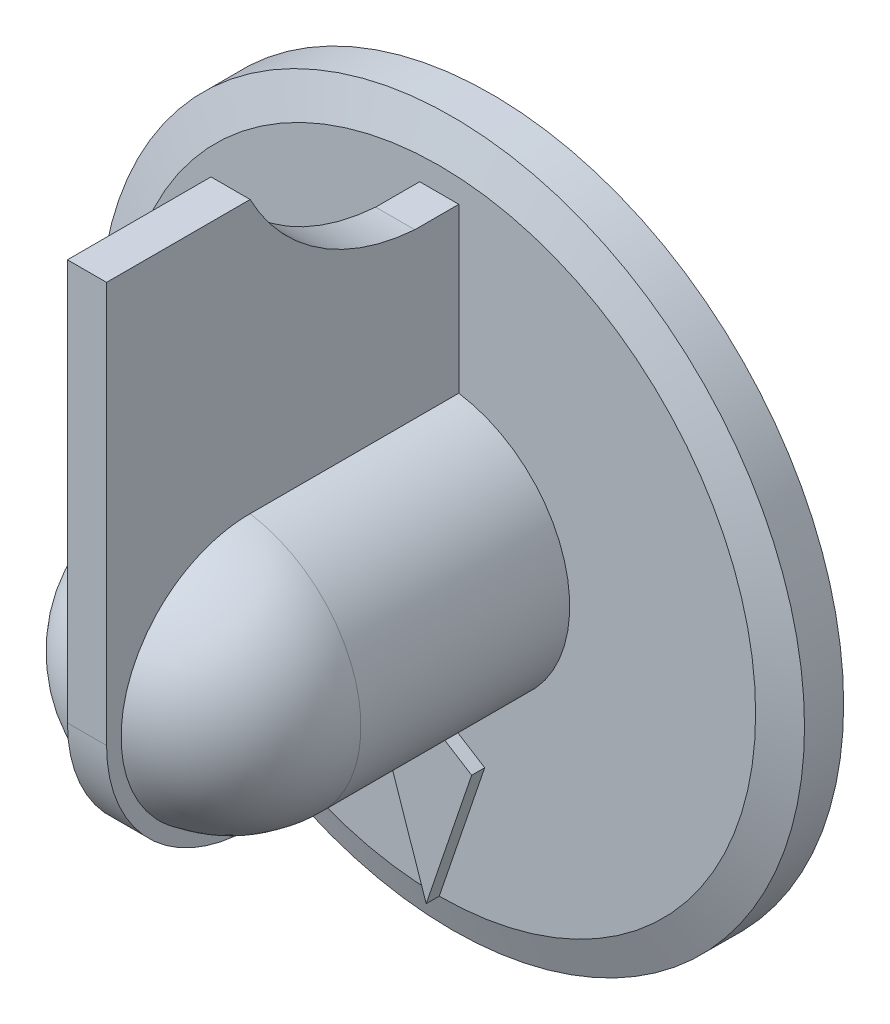
SolidWorks part; units mm, degrees
ref_plane "Front Plane" through (0, 0, 0) normal (0, 0, 1) x (1, 0, 0)
ref_plane "Top Plane" through (0, 0, 0) normal (0, 1, 0) x (1, 0, 0)
ref_plane "Right Plane" through (0, 0, 0) normal (1, 0, 0) x (0, 0, -1)
sketch "Sketch1" plane through (0, 0, 0) normal (0, 0, 1) x (1, 0, 0)
  circle A0 centre (0, 0) radius 13.5
  dimension "D1" = 27
extrude "Boss-Extrude1" add sketch "Sketch1" along normal blind 2
chamfer "Chamfer1" distance 0.5 angle 70 1 edges at (13.5, 0, 2)
sketch "Sketch2" plane through (0, 0, 2) normal (0, 0, 1) x (1, 0, 0)
  circle A0 centre (0, 0) radius 5
  dimension "D1" = 10
extrude "Boss-Extrude2" add sketch "Sketch2" along normal blind 8
sketch "Sketch3" plane through (0, 0, 10) normal (0, 0, 1) x (1, 0, 0)
  line L0 (0, 5) -> (0, -5)
  circle A0 centre (0, 0) radius 5 construction
  arc A1 (0, 5) -> (0, -5) centre (0, 0) ccw
revolve "Revolve6" add sketch "Sketch3" angle 360 about L0
sketch "Sketch4" plane through (0, 0, 0) normal (1, 0, 0) x (0, 0, -1)
  line L0 (-10, -5) -> (-2, -5) construction
  line L1 (-10, -5) -> (-2, -5) construction
  line L2 (0, 0) -> (-16.9265, 0) construction
  line L3 (-10, -5.5) -> (-2, -5.5)
  line L4 (-15.5, 0) -> (-15.5, 15.3718)
  line L5 (-15.5, 15.3718) -> (-9.9975, 15.3718)
  line L6 (-2, 11.2129) -> (-2, -5.5)
  line L7 (-2, 12.1263) -> (-2, -12.1263) construction
  line L8 (-2, 11.2129) -> (-3.6857, 11.2129)
  arc A0 (-10, 5) -> (-10, -5) centre (-10, 0) ccw construction
  arc A1 (-15, 0) -> (-10, -5) centre (-10, 0) ccw construction
  arc A2 (-15.5, 0) -> (-10, -5.5) centre (-10, 0) ccw
  arc A3 (-9.9975, 15.3718) -> (-3.6857, 11.2129) centre (-3.1316, 18.9229) ccw
  dimension "D1" = 0.5
extrude "Boss-Extrude3" add sketch "Sketch4" along normal mid plane 1.5
sketch "Sketch6" plane through (0, 0, 0) normal (0, 0, -1) x (-1, 0, 0)
  line L0 (0, 0) -> (0, 2.75) construction
  arc A0 (-1.9413, 1.9478) -> (-2.2553, 1.5736) centre (0, 0) ccw
  arc A2 (0.2351, 2.7399) -> (-0.2351, 2.7399) centre (0, 2.825) ccw
  arc A3 (1.158, 2.4943) -> (0.7162, 2.6551) centre (0.9662, 2.6546) ccw
  arc A4 (1.9413, 1.9478) -> (1.5811, 2.25) centre (1.8159, 2.1641) ccw
  arc A5 (2.4904, 1.1664) -> (2.2553, 1.5736) centre (2.4465, 1.4125) ccw
  arc A6 (2.7391, 0.2443) -> (2.6575, 0.7073) centre (2.7821, 0.4906) ccw
  arc A7 (2.6575, -0.7073) -> (2.7391, -0.2443) centre (2.7821, -0.4906) ccw
  arc A8 (2.2553, -1.5736) -> (2.4904, -1.1664) centre (2.4465, -1.4125) ccw
  arc A9 (1.5811, -2.25) -> (1.9413, -1.9478) centre (1.8159, -2.1641) ccw
  arc A10 (0.7162, -2.6551) -> (1.158, -2.4943) centre (0.9662, -2.6546) ccw
  arc A11 (-0.2351, -2.7399) -> (0.2351, -2.7399) centre (0, -2.825) ccw
  arc A12 (-1.158, -2.4943) -> (-0.7162, -2.6551) centre (-0.9662, -2.6546) ccw
  arc A13 (-1.9413, -1.9478) -> (-1.5811, -2.25) centre (-1.8159, -2.1641) ccw
  arc A14 (-2.4904, -1.1664) -> (-2.2553, -1.5736) centre (-2.4465, -1.4125) ccw
  arc A15 (-2.7391, -0.2443) -> (-2.6575, -0.7073) centre (-2.7821, -0.4906) ccw
  arc A16 (-2.6575, 0.7073) -> (-2.7391, 0.2443) centre (-2.7821, 0.4906) ccw
  arc A17 (-2.2553, 1.5736) -> (-2.4904, 1.1664) centre (-2.4465, 1.4125) ccw
  arc A18 (-1.5811, 2.25) -> (-1.9413, 1.9478) centre (-1.8159, 2.1641) ccw
  arc A19 (-0.7162, 2.6551) -> (-1.158, 2.4943) centre (-0.9662, 2.6546) ccw
  arc A20 (-1.158, 2.4943) -> (-1.5811, 2.25) centre (0, 0) ccw
  arc A21 (-0.2351, 2.7399) -> (-0.7162, 2.6551) centre (0, 0) ccw
  arc A22 (0.7162, 2.6551) -> (0.2351, 2.7399) centre (0, 0) ccw
  arc A23 (1.5811, 2.25) -> (1.158, 2.4943) centre (0, 0) ccw
  arc A24 (2.2553, 1.5736) -> (1.9413, 1.9478) centre (0, 0) ccw
  arc A25 (2.6575, 0.7073) -> (2.4904, 1.1664) centre (0, 0) ccw
  arc A26 (2.7391, -0.2443) -> (2.7391, 0.2443) centre (0, 0) ccw
  arc A27 (2.4904, -1.1664) -> (2.6575, -0.7073) centre (0, 0) ccw
  arc A28 (1.9413, -1.9478) -> (2.2553, -1.5736) centre (0, 0) ccw
  arc A29 (1.158, -2.4943) -> (1.5811, -2.25) centre (0, 0) ccw
  arc A30 (0.2351, -2.7399) -> (0.7162, -2.6551) centre (0, 0) ccw
  arc A31 (-0.7162, -2.6551) -> (-0.2351, -2.7399) centre (0, 0) ccw
  arc A32 (-1.5811, -2.25) -> (-1.158, -2.4943) centre (0, 0) ccw
  arc A33 (-2.2553, -1.5736) -> (-1.9413, -1.9478) centre (0, 0) ccw
  arc A34 (-2.6575, -0.7073) -> (-2.4904, -1.1664) centre (0, 0) ccw
  arc A35 (-2.7391, 0.2443) -> (-2.7391, -0.2443) centre (0, 0) ccw
  arc A36 (-2.4904, 1.1664) -> (-2.6575, 0.7073) centre (0, 0) ccw
  point P41 (0, 3.075)
  point P58 (0, -3.075)
  dimension "D1" = 5.5
  dimension "D3" = 0.5
  dimension "D2" = 2.825
  dimension "D5" = 3.075
  dimension "D6" = 6.15
  dimension "D4" = 18
extrude "Cut-Extrude1" cut sketch "Sketch6" against normal blind 9.5
sketch "Sketch7" plane through (0, 0, 2) normal (0, 0, 1) x (1, 0, 0)
  line L0 (0, -5.899) -> (-1.7422, -6.9911)
  line L1 (0, -5.899) -> (0, -12.1263) construction
  line L2 (-1.7422, -6.9911) -> (0, -12.1263)
  line L3 (1.7422, -6.9911) -> (0, -12.1263)
  line L4 (0, -5.899) -> (1.7422, -6.9911)
  circle A0 centre (0, 0) radius 12.1263 construction
extrude "Boss-Extrude4" add sketch "Sketch7" along normal mid plane 1
sketch "Sketch14" plane through (0, 0, 0) normal (0, 0, -1) x (-1, 0, 0)
  circle A0 centre (0, 0) radius 3.3
  dimension "D1" = 6.6
extrude "Cut-Extrude5" cut sketch "Sketch14" against normal blind 0.6
fillet "Fillet1" radius 0.1 108 edges at (1.375, 2.3816, 9.5) (1.0517, 2.8896, 9.5) (1.158, 2.4943, 5.05) (1.5811, 2.25, 5.05) (1.9766, 2.3556, 9.5) (0.4775, 2.7082, 9.5) (0.7162, 2.6551, 5.05) (0.4775, 2.7082, 0.6) (1.0517, 2.8896, 0.6) (1.375, 2.3816, 0.6) (1.9766, 2.3556, 0.6) (2.663, 1.5375, 9.5) (2.663, 1.5375, 0.6) (1.9413, 1.9478, 5.05) (2.1066, 1.7677, 9.5) (2.2553, 1.5736, 5.05) (2.1066, 1.7677, 0.6) (2.4904, 1.1664, 5.05) (2.5842, 0.9406, 9.5) (2.5842, 0.9406, 0.6) (2.6575, 0.7073, 5.05) (3.0283, 0.534, 9.5) (3.0283, 0.534, 0.6) (2.7391, 0.2443, 5.05) (2.75, 0, 9.5) (2.75, 0, 0.6) (2.7391, -0.2443, 5.05) (3.0283, -0.534, 9.5) (3.0283, -0.534, 0.6) (2.6575, -0.7073, 5.05) (2.5842, -0.9406, 9.5) (2.5842, -0.9406, 0.6) (2.4904, -1.1664, 5.05) (2.663, -1.5375, 9.5) (2.663, -1.5375, 0.6) (2.2553, -1.5736, 5.05) (2.1066, -1.7677, 9.5) (2.1066, -1.7677, 0.6) (1.9413, -1.9478, 5.05) (1.9766, -2.3556, 9.5) (1.9766, -2.3556, 0.6) (1.5811, -2.25, 5.05) (1.375, -2.3816, 9.5) (1.375, -2.3816, 0.6) (1.158, -2.4943, 5.05) (1.0517, -2.8896, 9.5) (1.0517, -2.8896, 0.6) (0.7162, -2.6551, 5.05) (0.4775, -2.7082, 9.5) (0.4775, -2.7082, 0.6) (0.2351, -2.7399, 5.05) (0, -3.075, 9.5) (0, -3.075, 0.6) (-0.2351, -2.7399, 5.05) (-0.4775, -2.7082, 9.5) (-0.4775, -2.7082, 0.6) (-0.7162, -2.6551, 5.05) (-1.0517, -2.8896, 9.5) (-1.0517, -2.8896, 0.6) (-1.158, -2.4943, 5.05) (-1.375, -2.3816, 9.5) (-1.375, -2.3816, 0.6) (-1.5811, -2.25, 5.05) (-1.9766, -2.3556, 9.5) (-1.9766, -2.3556, 0.6) (-1.9413, -1.9478, 5.05) (-2.1066, -1.7677, 9.5) (-2.1066, -1.7677, 0.6) (-2.2553, -1.5736, 5.05) (-2.663, -1.5375, 9.5) (-2.663, -1.5375, 0.6) (-2.4904, -1.1664, 5.05) (-2.5842, -0.9406, 9.5) (-2.5842, -0.9406, 0.6) (-2.6575, -0.7073, 5.05) (-3.0283, -0.534, 9.5) (-3.0283, -0.534, 0.6) (-2.7391, -0.2443, 5.05) (-2.75, 0, 9.5) (-2.75, 0, 0.6) (-2.7391, 0.2443, 5.05) (-3.0283, 0.534, 9.5) (-3.0283, 0.534, 0.6) (-2.6575, 0.7073, 5.05) (-2.5842, 0.9406, 9.5) (-2.5842, 0.9406, 0.6) (-2.4904, 1.1664, 5.05) (-2.663, 1.5375, 9.5) (-2.663, 1.5375, 0.6) (-2.2553, 1.5736, 5.05) (-2.1066, 1.7677, 9.5) (-2.1066, 1.7677, 0.6) (-1.9413, 1.9478, 5.05) (-1.9766, 2.3556, 9.5) (-1.9766, 2.3556, 0.6) (-1.5811, 2.25, 5.05) (-1.375, 2.3816, 9.5) (-1.375, 2.3816, 0.6) (-1.158, 2.4943, 5.05) (-1.0517, 2.8896, 9.5) (-1.0517, 2.8896, 0.6) (-0.7162, 2.6551, 5.05) (-0.4775, 2.7082, 9.5) (-0.4775, 2.7082, 0.6) (-0.2351, 2.7399, 5.05) (0, 3.075, 9.5) (0.2351, 2.7399, 5.05) (0, 3.075, 0.6)
fillet "Fillet2" radius 0.5 1 edges at (-3.3, 0, 0)
equation "\"D_puntas\"= 5.5"
equation "\"D_fondo\"= 6.15"
equation "\"D_ranura\"=0.5"
equation "\"D_BC\"= \"D_fondo\" - \"D_ranura\""
equation "\"Prof\"= 8"
equation "\"N_estrias\"= 18"
equation "\"D1@Sketch6\"=\"D_puntas\""
equation "\"D2@Sketch6\"=\"D_BC\"/2"
equation "\"D3@Sketch6\"=\"D_ranura\""
